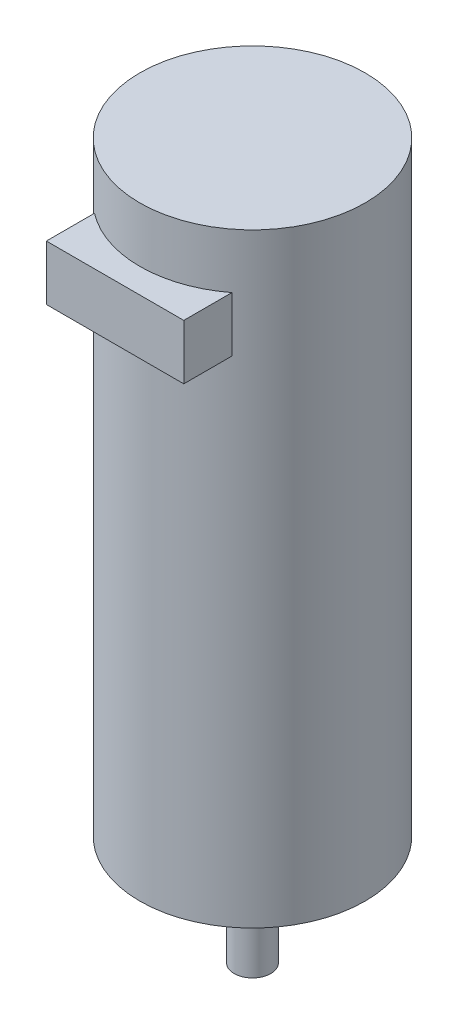
SolidWorks part; units mm, degrees
ref_plane "前视基准面" through (0, 0, 0) normal (0, 0, 1) x (1, 0, 0)
ref_plane "上视基准面" through (0, 0, 0) normal (0, 1, 0) x (1, 0, 0)
ref_plane "右视基准面" through (0, 0, 0) normal (1, 0, 0) x (0, 0, -1)
other "Configuration Table"
sketch "草图1" plane through (0, 0, 0) normal (0, 1, 0) x (1, 0, 0)
  circle A0 centre (0, 0) radius 12.3
  dimension "D1" = 24.6
extrude "凸台-拉伸1" add sketch "草图1" along normal blind 66
ref_plane "基准面1" through (0, 0, 5) normal (0, 0, 1) x (1, 0, 0)
sketch "草图2" plane through (0, 0, 5) normal (0, 0, 1) x (1, 0, 0)
  line L0 (12.3, 66) -> (-12.3, 66) construction
  line L1 (-7.5, 60) -> (7.5, 60)
  line L2 (-7.5, 60) -> (-7.5, 54)
  line L3 (-7.5, 54) -> (7.5, 54)
  line L4 (7.5, 60) -> (7.5, 54)
  line L5 (-12.3, 66) -> (-12.3, 0) construction
  dimension "D1" = 6
  dimension "D2" = 6
  dimension "D3" = 15
  dimension "D4" = 4.8
extrude "凸台-拉伸2" add sketch "草图2" along normal blind 10
sketch "草图3" plane through (0, 0, 0) normal (0, -1, 0) x (1, 0, 0)
  circle A0 centre (0, 0) radius 3.5
  dimension "D1" = 7
extrude "凸台-拉伸3" add sketch "草图3" along normal blind 2.5
sketch "草图4" plane through (0, -2.5, 0) normal (0, -1, 0) x (1, 0, 0)
  circle A0 centre (0, 0) radius 2
  dimension "D1" = 4
extrude "凸台-拉伸4" add sketch "草图4" along normal blind 9.5
sketch "草图5" plane through (0, 0, 0) normal (0, -1, 0) x (1, 0, 0)
  circle A0 centre (0, 8.5) radius 1.6
  circle A1 centre (0, -8.5) radius 1.6
  point P8 (0, 0)
  dimension "D2" = 3.2
  dimension "D1" = 8.5
  dimension "D3" = 2
extrude "切除-拉伸1" cut sketch "草图5" against normal blind 4
